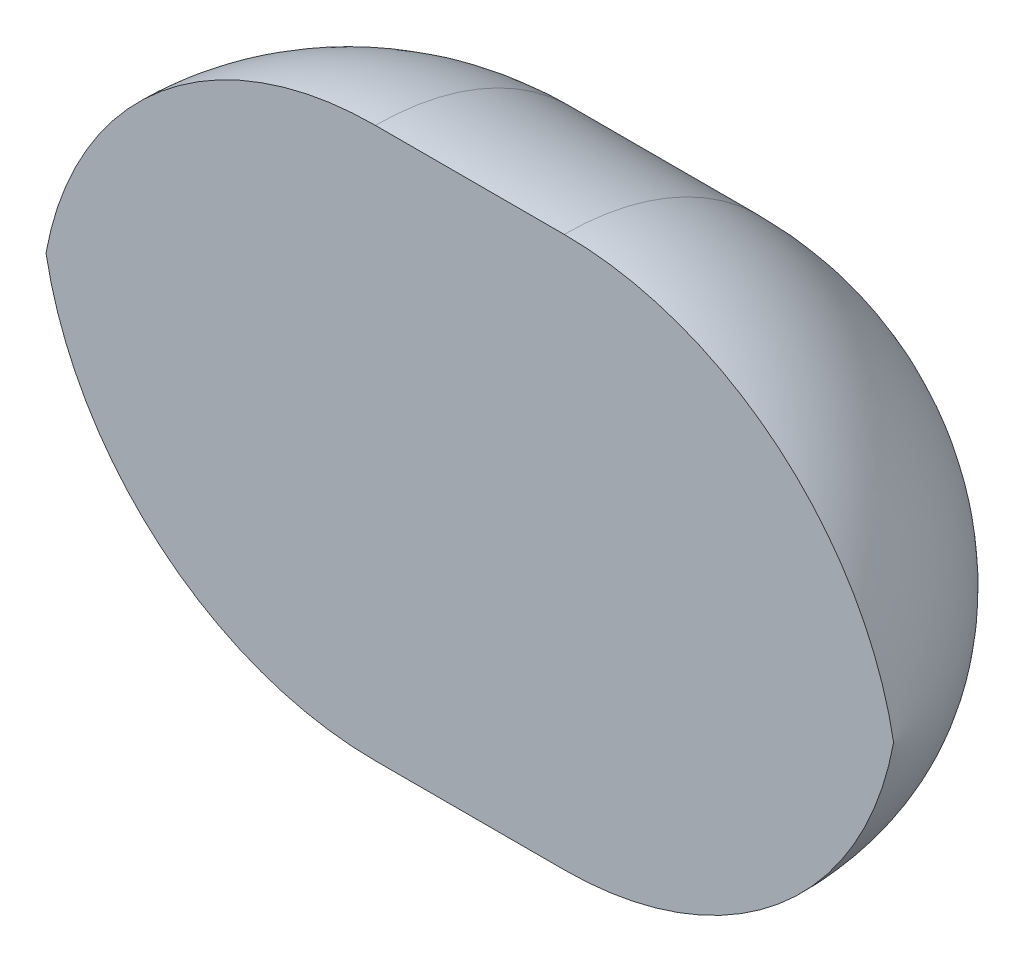
SolidWorks part; units mm, degrees
ref_plane "Front Plane" through (0, 0, 0) normal (0, 0, 1) x (1, 0, 0)
ref_plane "Top Plane" through (0, 0, 0) normal (0, 1, 0) x (1, 0, 0)
ref_plane "Right Plane" through (0, 0, 0) normal (1, 0, 0) x (0, 0, -1)
sketch "Sketch1" plane through (0, 0, 0) normal (0, 0, 1) x (1, 0, 0)
  line L0 (-31.9899, 9.7929) -> (-44.6502, 9.7929)
  line L2 (-36.91, 13.9029) -> (-39.73, 13.9029)
  arc A1 (-31.9899, 9.7929) -> (-36.91, 13.9029) centre (-36.91, 8.9029) ccw
  arc A2 (-39.73, 13.9029) -> (-44.6502, 9.7929) centre (-39.73, 8.9029) ccw
revolve "Revolve1" add sketch "Sketch1" angle 180 about L0
